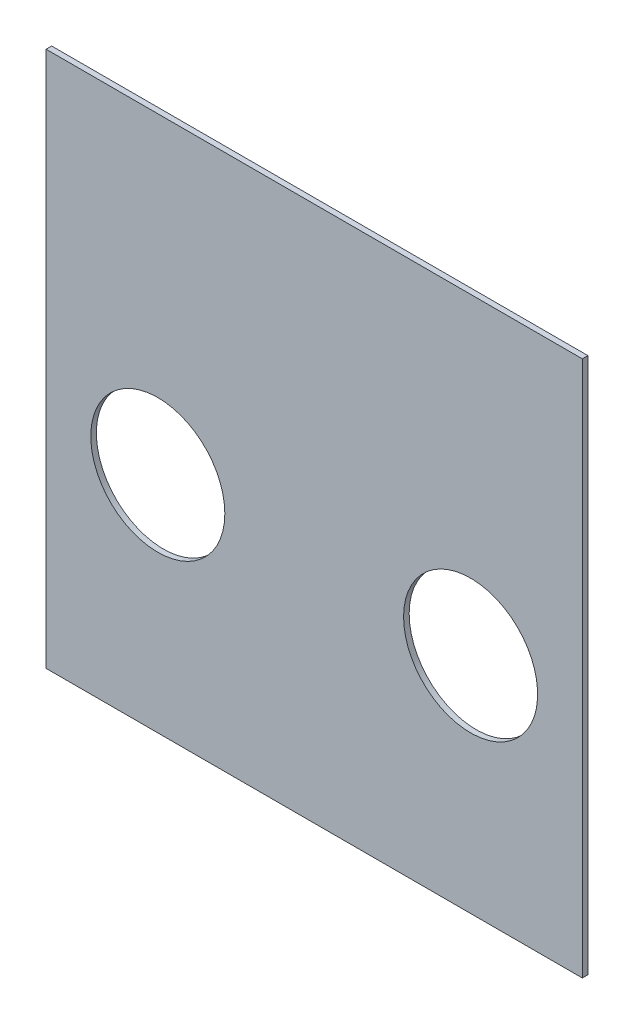
SolidWorks part; units mm, degrees
ref_plane "Front Plane" through (0, 0, 0) normal (0, 0, 1) x (1, 0, 0)
ref_plane "Top Plane" through (0, 0, 0) normal (0, 1, 0) x (1, 0, 0)
ref_plane "Right Plane" through (0, 0, 0) normal (1, 0, 0) x (0, 0, -1)
sketch "Sketch1" plane through (0, 0, 0) normal (0, 0, 1) x (1, 0, 0)
  line L1 (-304.8, -304.8) -> (304.8, -304.8)
  line L2 (-304.8, -304.8) -> (-304.8, 304.8)
  line L3 (-304.8, 304.8) -> (304.8, 304.8)
  line L4 (304.8, -304.8) -> (304.8, 304.8)
  line L5 (-304.8, -304.8) -> (304.8, 304.8) construction
  line L6 (-304.8, 304.8) -> (304.8, -304.8) construction
  point P0 (0, 0)
  dimension "D1" = 609.6
  dimension "D2" = 609.6
extrude "Boss-Extrude1" add sketch "Sketch1" along normal blind 6.35
sketch "Sketch2" plane through (0, 0, 6.35) normal (0, 0, 1) x (1, 0, 0)
  line L0 (0, 304.8) -> (0, -304.8) construction
  line L1 (304.8, 304.8) -> (-304.8, 304.8) construction
  line L2 (-304.8, -304.8) -> (304.8, -304.8) construction
  circle A1 centre (-177.8, -50.8) radius 76.2
  circle A2 centre (177.8, -50.8) radius 76.2
  dimension "D1" = 355.6
  dimension "D2" = 152.4
  dimension "D3" = 355.6
extrude "Cut-Extrude1" cut sketch "Sketch2" against normal through all
